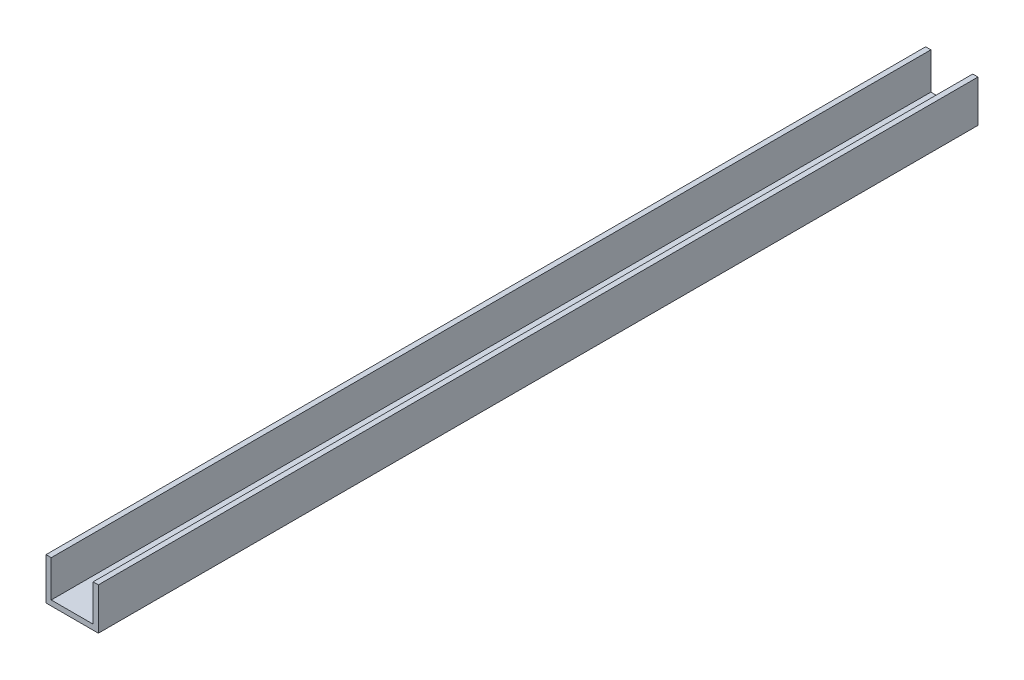
SolidWorks part; units mm, degrees
ref_plane "Front Plane" through (0, 0, 0) normal (0, 0, 1) x (1, 0, 0)
ref_plane "Top Plane" through (0, 0, 0) normal (0, 1, 0) x (1, 0, 0)
ref_plane "Right Plane" through (0, 0, 0) normal (1, 0, 0) x (0, 0, -1)
other "Configuration Table"
sketch "Sketch1" plane through (0, 0, 0) normal (0, 0, 1) x (1, 0, 0)
  line L0 (0, 0) -> (0, 12.7)
  line L1 (0, 12.7) -> (1.5875, 12.7)
  line L2 (1.5875, 12.7) -> (1.5875, 1.5875)
  line L3 (1.5875, 1.5875) -> (14.2875, 1.5875)
  line L4 (14.2875, 1.5875) -> (14.2875, 12.7)
  line L5 (14.2875, 12.7) -> (15.875, 12.7)
  line L6 (15.875, 12.7) -> (15.875, 0)
  line L7 (15.875, 0) -> (0, 0)
  line L8 (0, 0) -> (1.5875, 1.5875) construction
  dimension "D1" = 45
  dimension "D2" = 1.5875
  dimension "D3" = 15.875
  dimension "D4" = 12.7
extrude "Boss-Extrude1" add sketch "Sketch1" along normal blind 266.7
